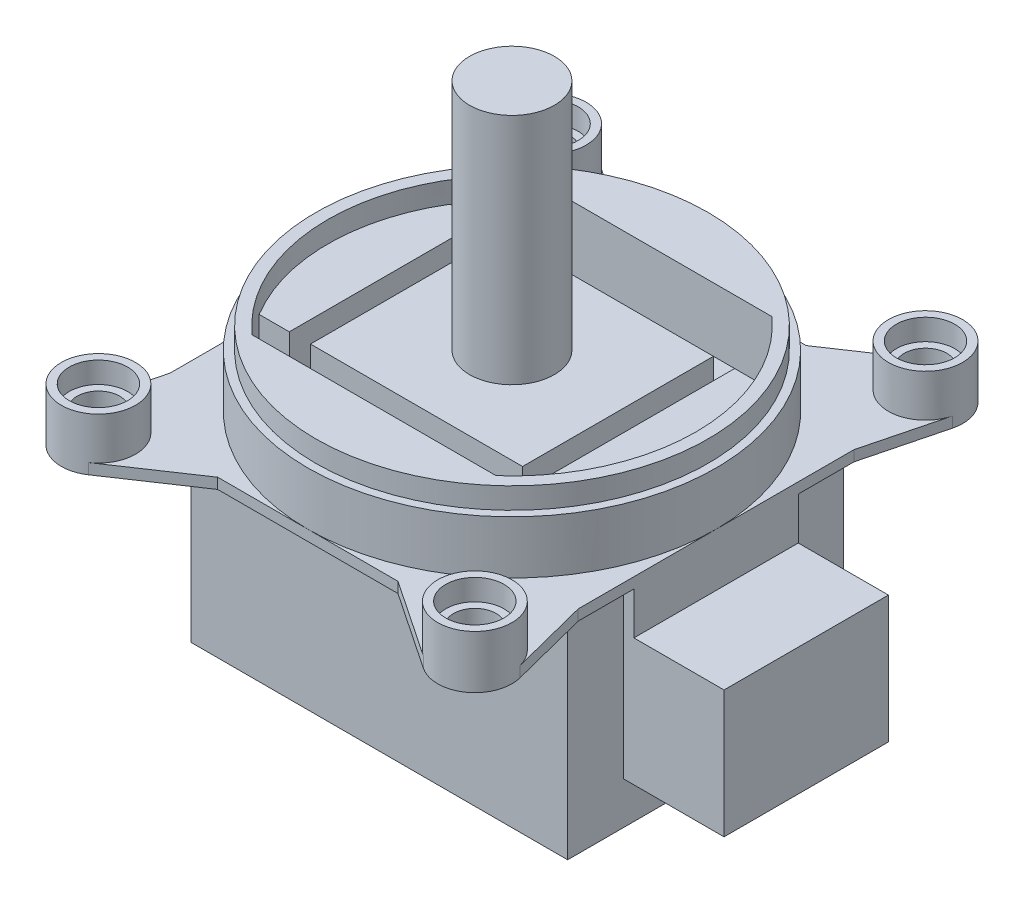
SolidWorks part; units mm, degrees
ref_plane "Front Plane" through (0, 0, 0) normal (0, 0, 1) x (1, 0, 0)
ref_plane "Top Plane" through (0, 0, 0) normal (0, 1, 0) x (1, 0, 0)
ref_plane "Right Plane" through (0, 0, 0) normal (1, 0, 0) x (0, 0, -1)
sketch "Sketch4" plane through (0, 0, 0) normal (0, 1, 0) x (1, 0, 0)
  line L0 (-15.7976, 24.1548) -> (-8.5, 19.25)
  line L1 (21.25, -24.75) -> (-21.25, -24.75)
  line L2 (21.25, -24.75) -> (21.25, 24.75)
  line L3 (21.25, 24.75) -> (-21.25, 24.75)
  line L4 (-21.25, -24.75) -> (-21.25, 24.75)
  line L5 (21.25, -24.75) -> (-21.25, 24.75) construction
  line L6 (21.25, 24.75) -> (-21.25, -24.75) construction
  line L11 (0, 0) -> (0, 19.25) construction
  line L12 (16.5278, 19.25) -> (-15.7681, -18.3652) construction
  line L13 (-8.5, 19.25) -> (8.5, 19.25)
  line L14 (8.5, 19.25) -> (15.7976, 24.1548)
  line L15 (21.1406, 20.3816) -> (19.25, 13)
  line L16 (19.25, 13) -> (19.25, -13)
  line L17 (19.25, -13) -> (21.1406, -20.3816)
  line L18 (-15.7976, -24.1548) -> (-8.5, -19.25)
  line L19 (-8.5, -19.25) -> (8.5, -19.25)
  line L20 (8.5, -19.25) -> (15.7976, -24.1548)
  line L21 (-21.1406, -20.3816) -> (-19.25, -13)
  line L22 (-19.25, -13) -> (-19.25, 13)
  line L23 (-19.25, 13) -> (-21.1406, 20.3816)
  line L24 (0, 0) -> (19.25, 0) construction
  line L25 (19.25, 0) -> (0, 0) construction
  line L26 (0, 0) -> (0, 19.25) construction
  line L28 (8.5, -19.25) -> (-8.5, -19.25)
  line L29 (-19.25, -13) -> (-19.25, 13)
  line L30 (8.5, 19.25) -> (-8.5, 19.25)
  circle A0 centre (0, 0) radius 19.25
  circle A1 centre (-17.75, 21.25) radius 3.5
  circle A2 centre (17.75, 21.25) radius 3.5
  circle A3 centre (17.75, -21.25) radius 3.5
  circle A4 centre (-17.75, -21.25) radius 3.5
  point P0 (0, 0)
  point P6 (0, 0)
  dimension "D4" = 7
  dimension "D16" = 38.5
  dimension "D1" = 42.5
  dimension "D2" = 49.5
  dimension "D3" = 2
  dimension "D5" = 17
  dimension "D6" = 8.5
  dimension "D7" = 26
  dimension "D8" = 13
  dimension "D9" = 17
  dimension "D10" = 8.5
  dimension "D11" = 26
  dimension "D12" = 13
  dimension "D13" = 2
  dimension "D14" = 5.5
  dimension "D15" = 5.5
  dimension "D17" = 7.3816
extrude "Boss-Extrude1" add sketch "Sketch4" along normal blind 1 contours A4 | A4 L18 L19 A0 L22 L21 | A0 | A3 L17 L16 A0 L28 L20 | A3 | A2 L14 L30 A0 L16 L15 | A2 | A1 L23 L29 A0 L13 L0 | A1
sketch "Sketch5" plane through (0, 1, 0) normal (0, 1, 0) x (1, 0, 0)
  circle A0 centre (0, 0) radius 19.25
  dimension "D1" = 38.5
extrude "Boss-Extrude2" add sketch "Sketch5" along normal blind 5
sketch "Sketch6" plane through (0, 6, 0) normal (0, 1, 0) x (1, 0, 0)
  circle A0 centre (0, 0) radius 18.5
  dimension "D1" = 37
extrude "Boss-Extrude3" add sketch "Sketch6" along normal blind 2
sketch "Sketch7" plane through (0, 8, 0) normal (0, 1, 0) x (1, 0, 0)
  line L0 (-11.5, 13) -> (11.5, 13)
  line L1 (-11.5, -13) -> (11.5, -13)
  arc A0 (-11.5, 13) -> (-11.5, -13) centre (0, 0) ccw
  arc A1 (11.5, -13) -> (11.5, 13) centre (0, 0) ccw
  dimension "D1" = 13
  dimension "D2" = 23
  dimension "D3" = 26
extrude "Cut-Extrude1" cut sketch "Sketch7" against normal blind 6
sketch "Sketch8" plane through (0, 2, 0) normal (0, 1, 0) x (1, 0, 0)
  line L1 (10.5, -13) -> (-10.5, -13)
  line L2 (10.5, -13) -> (10.5, 13)
  line L3 (10.5, 13) -> (-10.5, 13)
  line L4 (-10.5, -13) -> (-10.5, 13)
  line L5 (10.5, -13) -> (-10.5, 13) construction
  line L6 (10.5, 13) -> (-10.5, -13) construction
  line L7 (11.5, -12.5) -> (-11.5, -12.5)
  line L8 (11.5, -12.5) -> (11.5, 12.5)
  line L9 (11.5, 12.5) -> (-11.5, 12.5)
  line L10 (-11.5, -12.5) -> (-11.5, 12.5)
  line L11 (11.5, -12.5) -> (-11.5, 12.5) construction
  line L12 (11.5, 12.5) -> (-11.5, -12.5) construction
  point P0 (0, 0)
  point P6 (0, 0)
  dimension "D1" = 21
  dimension "D2" = 26
  dimension "D3" = 23
  dimension "D4" = 25
extrude "Cut-Extrude2" cut sketch "Sketch8" against normal blind 6 contours L10 L7 L4 L9 | L8 L9 L2 L7
sketch "Sketch9" plane through (0, 2, 0) normal (0, 1, 0) x (1, 0, 0)
  line L0 (-10.5, -12.5) -> (-10.5, 12.5) construction
  line L1 (10, -9) -> (-10, -9)
  line L2 (10, -9) -> (10, 9)
  line L3 (10, 9) -> (-10, 9)
  line L4 (-10, -9) -> (-10, 9)
  line L5 (10, -9) -> (-10, 9) construction
  line L6 (10, 9) -> (-10, -9) construction
  line L7 (11.5, 13) -> (-11.5, 13) construction
  line L8 (0, 13) -> (0, -9) construction
  line L9 (-14.8408, 9) -> (-12, 9)
  line L10 (-12, 9) -> (-12, -9)
  line L11 (-12, -9) -> (-14.8408, -9)
  line L12 (-11.5, -12.5) -> (-11.5, 12.5) construction
  line L13 (11.5, 13) -> (-11.5, 13) construction
  line L14 (12, -9) -> (14.8408, -9)
  line L15 (12, 9) -> (12, -9)
  line L16 (14.8408, 9) -> (12, 9)
  arc A0 (-11.5, 13) -> (-11.5, -13) centre (0, 0) ccw construction
  arc A1 (-11.5, 13) -> (-11.5, -13) centre (0, 0) ccw construction
  arc A2 (-14.8408, 9) -> (-14.8408, -9) centre (0, 0) ccw
  arc A3 (14.8408, 9) -> (14.8408, -9) centre (0, 0) cw
  point P0 (0, 0)
  dimension "D1" = 0.5
  dimension "D2" = 4
  dimension "D3" = 0.5
  dimension "D4" = 2.8408
extrude "Boss-Extrude4" add sketch "Sketch9" along normal blind 4
sketch "Sketch10" plane through (0, 6, 0) normal (0, 1, 0) x (1, 0, 0)
  circle A0 centre (0, 0) radius 4
  dimension "D1" = 8
extrude "Boss-Extrude5" add sketch "Sketch10" along normal blind 22
sketch "Sketch11" plane through (0, 1, 0) normal (0, 1, 0) x (1, 0, 0)
  circle A0 centre (-17.75, 21.25) radius 3.5
  circle A1 centre (17.75, 21.25) radius 3.5
  circle A2 centre (17.75, -21.25) radius 3.5
  circle A3 centre (-17.75, -21.25) radius 3.5
  dimension "D1" = 7
extrude "Boss-Extrude6" add sketch "Sketch11" along normal blind 4
sketch "Sketch12" plane through (0, 5, 0) normal (0, 1, 0) x (1, 0, 0)
  circle A0 centre (-17.75, 21.25) radius 2.75
  circle A1 centre (17.75, 21.25) radius 2.75
  circle A2 centre (17.75, -21.25) radius 2.75
  circle A3 centre (-17.75, -21.25) radius 2.75
  dimension "D1" = 5.5
extrude "Cut-Extrude3" cut sketch "Sketch12" against normal blind 2
sketch "Sketch13" plane through (0, 3, 0) normal (0, 1, 0) x (1, 0, 0)
  circle A0 centre (-17.75, 21.25) radius 1.5
  circle A1 centre (17.75, 21.25) radius 1.5
  circle A2 centre (17.75, -21.25) radius 1.5
  circle A3 centre (-17.75, -21.25) radius 1.5
  dimension "D1" = 3
extrude "Cut-Extrude4" cut sketch "Sketch13" against normal blind 7
sketch "Sketch14" plane through (0, 0, 0) normal (0, -1, 0) x (1, 0, 0)
  line L0 (-19.25, 13) -> (-19.25, -13) construction
  line L1 (18.25, -13) -> (-17.25, -13)
  line L2 (18.25, -13) -> (18.25, 13)
  line L3 (18.25, 13) -> (-17.25, 13)
  line L4 (-17.25, -13) -> (-17.25, 13)
  line L5 (19.25, -13) -> (19.25, 13) construction
  point P0 (0, 0)
  dimension "D1" = 2
  dimension "D2" = 1
  dimension "D3" = 26
  dimension "D4" = 13
extrude "Boss-Extrude7" add sketch "Sketch14" along normal blind 20
sketch "Sketch15" plane through (18.25, 0, 0) normal (1, 0, 0) x (0, 0, -1)
  line L0 (-7.75, 0) -> (-7.75, -16)
  line L1 (13, 0) -> (-13, 0) construction
  line L2 (-7.75, -16) -> (7.75, -16)
  line L3 (7.75, -16) -> (7.75, 0)
  line L5 (-7.75, 0) -> (-7.75, 1)
  line L6 (-7.75, 1) -> (7.75, 1)
  line L7 (7.75, 1) -> (7.75, 0)
  dimension "D1" = 17
  dimension "D2" = 7.75
  dimension "D3" = 1
  dimension "D4" = 15.5
extrude "Boss-Extrude8" add sketch "Sketch15" along normal blind 9.5
sketch "Sketch16" plane through (27.75, 0, 0) normal (1, 0, 0) x (0, 0, -1)
  line L0 (-7.75, 1) -> (-7.75, -4)
  line L1 (-7.75, 1) -> (-7.75, -16) construction
  line L2 (-7.75, -4) -> (7.75, -4)
  line L3 (7.75, -16) -> (7.75, 0) construction
  line L4 (7.75, -4) -> (7.75, 1)
  line L5 (7.75, 1) -> (-7.75, 1)
  dimension "D1" = 5
extrude "Cut-Extrude5" cut sketch "Sketch16" against normal blind 8.5
sketch "Sketch17" plane through (0, 0, 0) normal (0, -1, 0) x (1, 0, 0)
  circle A0 centre (-17.75, 21.25) radius 2
  circle A1 centre (17.75, 21.25) radius 2
  circle A2 centre (17.75, -21.25) radius 2
  circle A3 centre (-17.75, -21.25) radius 2
  dimension "D1" = 4
extrude "Cut-Extrude6" cut sketch "Sketch17" against normal blind 4
